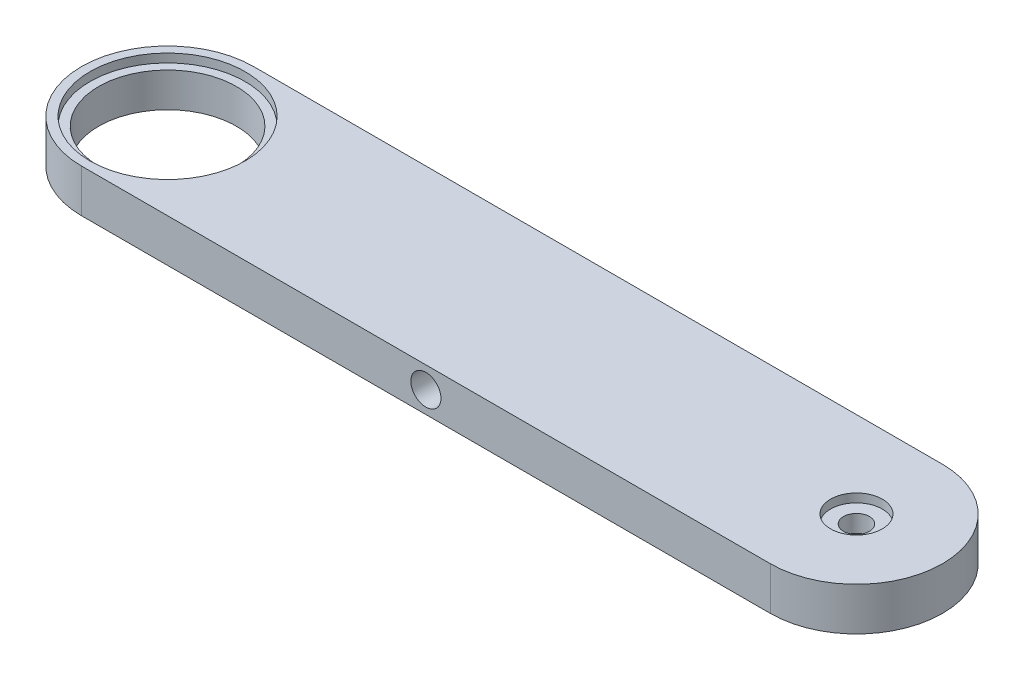
SolidWorks part; units mm, degrees
ref_plane "Front Plane" through (0, 0, 0) normal (0, 0, 1) x (1, 0, 0)
ref_plane "Top Plane" through (0, 0, 0) normal (0, 1, 0) x (1, 0, 0)
ref_plane "Right Plane" through (0, 0, 0) normal (1, 0, 0) x (0, 0, -1)
sketch "Sketch1" plane through (0, 0, 0) normal (0, 1, 0) x (1, 0, 0)
  line L1 (-40, 10) -> (40, 10)
  line L3 (-40, -10) -> (40, -10)
  arc A0 (40, -10) -> (40, 10) centre (40, 0) ccw
  arc A1 (-40, 10) -> (-40, -10) centre (-40, 0) ccw
  point P0 (0, 0)
  dimension "D1" = 80
  dimension "D2" = 20
extrude "Boss-Extrude1" add sketch "Sketch1" along normal blind 5
sketch "Sketch2" plane through (0, 5, 0) normal (0, 1, 0) x (1, 0, 0)
  line L0 (-40, 10) -> (-40, -10)
  circle A0 centre (-40, 0) radius 8
  dimension "D1" = 16
extrude "Cut-Extrude1" cut sketch "Sketch2" against normal through all contours L0 A0 | L0 A0
sketch "Sketch3" plane through (0, 5, 0) normal (0, 1, 0) x (1, 0, 0)
  circle A0 centre (-40, 0) radius 9
  dimension "D1" = 18
extrude "Cut-Extrude2" cut sketch "Sketch3" against normal blind 1
sketch "Sketch4" plane through (0, 5, 0) normal (0, 1, 0) x (1, 0, 0)
  line L0 (40, 10) -> (40, 3)
  line L1 (40, -3) -> (40, -10)
  circle A0 centre (40, 0) radius 3
  line M6 (-40, -10) -> (40, -10)
  dimension "D1" = 6
extrude "Cut-Extrude3" cut sketch "Sketch4" against normal blind 1 contours A0 M6
sketch "Sketch5" plane through (0, 4, 0) normal (0, 1, 0) x (1, 0, 0)
  circle A0 centre (40, 0) radius 1.5
  dimension "D1" = 3
extrude "Cut-Extrude4" cut sketch "Sketch5" against normal through all
sketch "Sketch6" plane through (0, 0, 0) normal (0, -1, 0) x (1, 0, 0)
  circle A0 centre (40, 0) radius 4
  dimension "D1" = 8
extrude "Cut-Extrude5" cut sketch "Sketch6" against normal blind 2
sketch "Sketch8" plane through (0, 0, 10) normal (0, 0, 1) x (1, 0, 0)
  circle A0 centre (0, 2.5) radius 1.75
  point P0 (0, 0)
  point P1 (0, 2.5)
  dimension "D2" = 3.5
  dimension "D1" = 2.5
extrude "Cut-Extrude7" cut sketch "Sketch8" against normal blind 10
